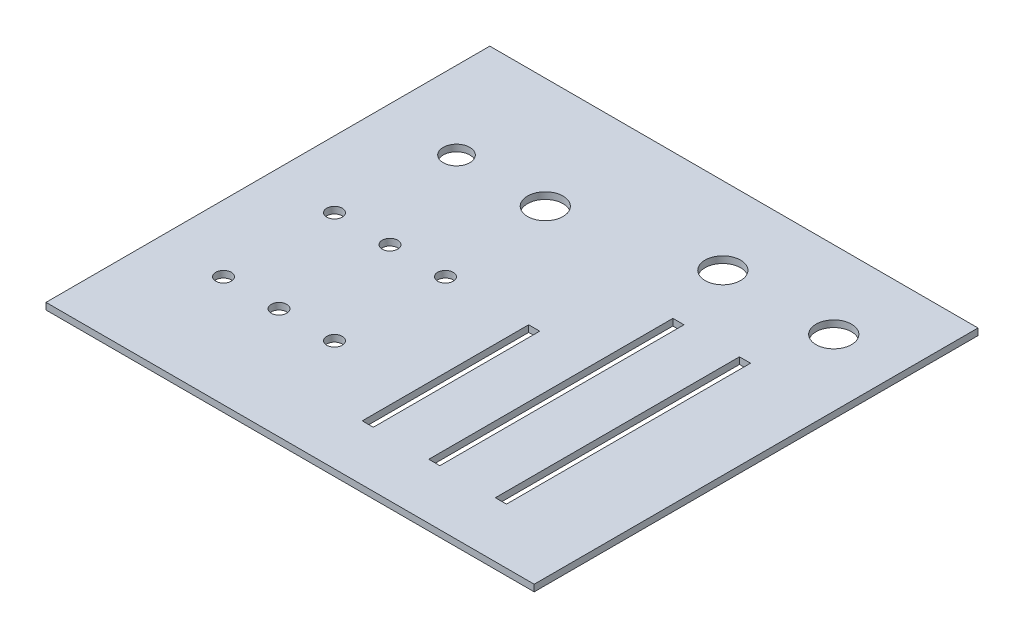
SolidWorks part; units mm, degrees
ref_plane "Plano frontal" through (0, 0, 0) normal (0, 0, 1) x (1, 0, 0)
ref_plane "Plano superior" through (0, 0, 0) normal (0, 1, 0) x (1, 0, 0)
ref_plane "Plano direito" through (0, 0, 0) normal (1, 0, 0) x (0, 0, -1)
sketch "Esboço2" plane through (0, 0, 0) normal (0, 1, 0) x (1, 0, 0)
  line L1 (110, 100) -> (-110, 100)
  line L2 (110, 100) -> (110, -100)
  line L3 (110, -100) -> (-110, -100)
  line L4 (-110, 100) -> (-110, -100)
  line L5 (110, 100) -> (-110, -100) construction
  line L6 (110, -100) -> (-110, 100) construction
  point P0 (0, 0)
  dimension "D1" = 200
  dimension "D2" = 220
extrude "Ressalto-extrusão1" add sketch "Esboço2" along normal blind 3
sketch "Esboço3" plane through (0, 3, 0) normal (0, 1, 0) x (1, 0, 0)
  line L0 (-110, 100) -> (-110, -100) construction
  line L1 (100, 90) -> (-100, 90) construction
  line L2 (100, 90) -> (100, -90) construction
  line L3 (100, -90) -> (-100, -90) construction
  line L4 (-100, 90) -> (-100, -90) construction
  line L5 (100, 90) -> (-100, -90) construction
  line L6 (100, -90) -> (-100, 90) construction
  line L7 (110, 100) -> (-110, 100) construction
  line L8 (-10, 90) -> (-10, -90) construction
  line L9 (-10, 0) -> (-100, 0) construction
  line L10 (-10, -50) -> (-100, -50) construction
  line L11 (-80, 0) -> (-80, -90) construction
  line L12 (-55, 0) -> (-55, -90) construction
  line L13 (-30, 0) -> (-30, -90) construction
  line L14 (-75, 0) -> (-75, 90) construction
  line L15 (-35, 0) -> (-35, 90) construction
  line L16 (-100, 50) -> (-10, 50) construction
  line L17 (-10, 65) -> (100, 65) construction
  line L18 (30, 90) -> (30, 65) construction
  line L19 (80, 90) -> (80, 65) construction
  line L21 (67.5, 35) -> (72.5, 35)
  line L22 (67.5, 35) -> (67.5, -75)
  line L23 (67.5, -75) -> (72.5, -75)
  line L24 (72.5, 35) -> (72.5, -75)
  line L25 (67.5, 35) -> (72.5, -75) construction
  line L26 (67.5, -75) -> (72.5, 35) construction
  line L27 (37.5, 35) -> (42.5, 35)
  line L28 (37.5, 35) -> (37.5, -75)
  line L29 (37.5, -75) -> (42.5, -75)
  line L30 (42.5, 35) -> (42.5, -75)
  line L31 (37.5, 35) -> (42.5, -75) construction
  line L32 (37.5, -75) -> (42.5, 35) construction
  line L33 (7.5, -75) -> (12.5, -75)
  line L34 (7.5, -75) -> (7.5, 0)
  line L35 (7.5, 0) -> (12.5, 0)
  line L36 (12.5, -75) -> (12.5, 0)
  line L37 (7.5, -75) -> (12.5, 0) construction
  line L38 (7.5, 0) -> (12.5, -75) construction
  circle A0 centre (-80, 0) radius 3.5
  circle A1 centre (-55, 0) radius 3.5
  circle A2 centre (-30, 0) radius 3.5
  circle A3 centre (-80, -50) radius 3.5
  circle A4 centre (-55, -50) radius 3.5
  circle A5 centre (-30, -50) radius 3.5
  circle A6 centre (-75, 50) radius 6
  circle A7 centre (-35, 50) radius 8
  circle A8 centre (30, 65) radius 8
  circle A9 centre (80, 65) radius 8
  point P0 (0, 0)
  point P48 (70, -20)
  point P53 (40, -20)
  point P58 (10, -37.5)
  dimension "D11" = 7
  dimension "D15" = 16
  dimension "D16" = 12
  dimension "D1" = 10
  dimension "D2" = 10
  dimension "D3" = 180
  dimension "D4" = 200
  dimension "D5" = 90
  dimension "D6" = 90
  dimension "D7" = 50
  dimension "D8" = 20
  dimension "D9" = 25
  dimension "D10" = 25
  dimension "D12" = 40
  dimension "D13" = 25
  dimension "D14" = 40
  dimension "D17" = 25
  dimension "D18" = 50
  dimension "D19" = 20
  dimension "D20" = 110
  dimension "D21" = 15
  dimension "D22" = 75
  dimension "D23" = 5
  dimension "D24" = 5
  dimension "D25" = 5
  dimension "D26" = 30
  dimension "D27" = 30
  dimension "D28" = 30
extrude "Corte-extrusão1" cut sketch "Esboço3" against normal through all
